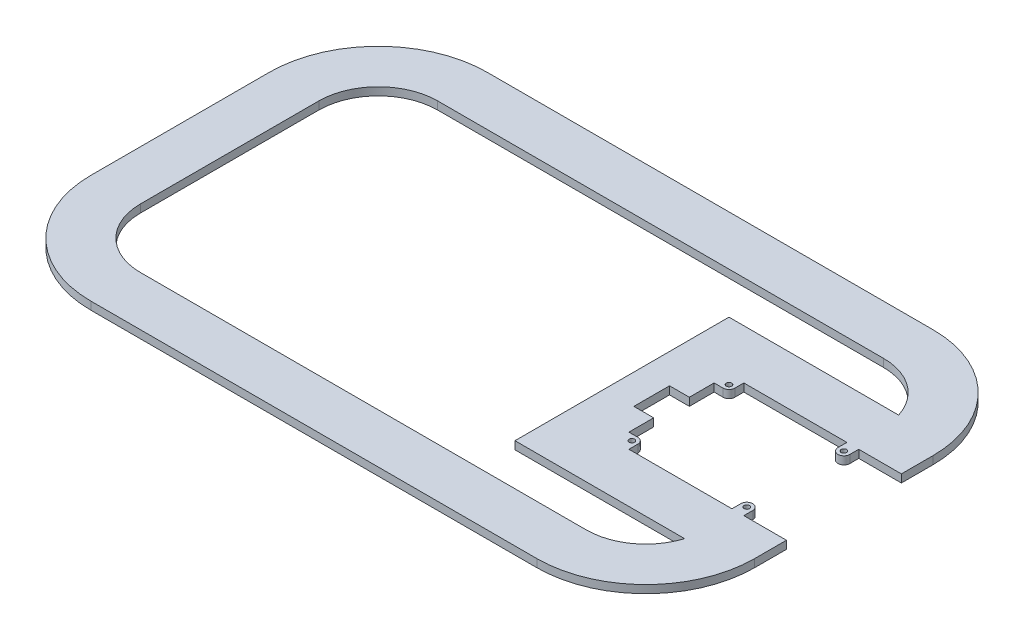
SolidWorks part; units mm, degrees
ref_plane "Front Plane" through (0, 0, 0) normal (0, 0, 1) x (1, 0, 0)
ref_plane "Top Plane" through (0, 0, 0) normal (0, 1, 0) x (1, 0, 0)
ref_plane "Right Plane" through (0, 0, 0) normal (1, 0, 0) x (0, 0, -1)
sketch "Sketch1" plane through (0, 0, 0) normal (0, 1, 0) x (1, 0, 0)
  line L0 (55, 25) -> (280, 25)
  line L1 (55, 0) -> (280, 0)
  line L2 (0, 55) -> (0, 145)
  line L3 (55, 200) -> (280, 200)
  line L4 (335, 145) -> (335, 129)
  line L5 (335, 55) -> (335, 71)
  line L6 (308.6182, 46) -> (308.6182, 46)
  line L7 (223, 46) -> (308.6182, 46)
  line L8 (335, 129) -> (313.5, 129)
  line L9 (223, 154) -> (223, 46)
  line L10 (308.6182, 154) -> (223, 154)
  line L11 (248, 121.5) -> (248, 109)
  line L12 (255.5, 71) -> (307.5, 71)
  line L13 (308.6182, 154) -> (308.6182, 154)
  line L14 (55, 175) -> (280, 175)
  line L15 (25, 55) -> (25, 145)
  line L16 (255.5, 124.5) -> (255.5, 129)
  line L17 (252.5, 121.5) -> (248, 121.5)
  line L18 (248, 129) -> (248, 71) construction
  line L19 (335, 129) -> (248, 129) construction
  line L20 (307.5, 124.5) -> (307.5, 129)
  line L21 (248, 100) -> (335, 100) construction
  line L22 (252.5, 78.5) -> (248, 78.5)
  line L23 (255.5, 75.5) -> (255.5, 71)
  line L24 (248, 71) -> (335, 71) construction
  line L25 (313.5, 124.5) -> (313.5, 129)
  line L26 (313.5, 75.5) -> (313.5, 71)
  line L27 (307.5, 75.5) -> (307.5, 71)
  line L28 (307.5, 129) -> (255.5, 129)
  line L29 (313.5, 71) -> (335, 71)
  line L32 (248, 109) -> (238, 109)
  line L33 (238, 109) -> (238, 91)
  line L34 (238, 91) -> (248, 91)
  line L35 (248, 91) -> (248, 78.5)
  arc A0 (55, 0) -> (0, 55) centre (55, 55) cw
  arc A1 (280, 0) -> (335, 55) centre (280, 55) ccw
  arc A2 (280, 200) -> (335, 145) centre (280, 145) cw
  arc A3 (0, 145) -> (55, 200) centre (55, 145) cw
  arc A4 (280, 25) -> (308.6182, 46) centre (280, 55) ccw
  arc A5 (280, 175) -> (308.6182, 154) centre (280, 145) cw
  arc A6 (25, 145) -> (55, 175) centre (55, 145) cw
  arc A7 (55, 25) -> (25, 55) centre (55, 55) cw
  circle A8 centre (252.5, 124.5) radius 1.375
  arc A9 (252.5, 121.5) -> (255.5, 124.5) centre (252.5, 124.5) ccw
  arc A10 (252.5, 78.5) -> (255.5, 75.5) centre (252.5, 75.5) cw
  circle A11 centre (252.5, 75.5) radius 1.375
  circle A12 centre (310.5, 124.5) radius 1.375
  arc A13 (307.5, 124.5) -> (313.5, 124.5) centre (310.5, 124.5) ccw
  arc A14 (307.5, 75.5) -> (313.5, 75.5) centre (310.5, 75.5) cw
  circle A15 centre (310.5, 75.5) radius 1.375
  point P7 (0, 0)
  point P15 (0, 200)
  point P28 (252.5, 124.5)
  point P43 (335, 137)
  point P45 (310.5, 124.5)
  dimension "D3" = 55
  dimension "D7" = 87
  dimension "D9" = 2.75
  dimension "D10" = 3
  dimension "D12" = 2.75
  dimension "D13" = 3
  dimension "D1" = 335
  dimension "D2" = 200
  dimension "D5" = 58
  dimension "D6" = 4.5
  dimension "D8" = 4.5
  dimension "D11" = 58
  dimension "D14" = 18
  dimension "D15" = 10
  dimension "D4" = 25
extrude "Boss-Extrude1" add sketch "Sketch1" along normal blind 4
